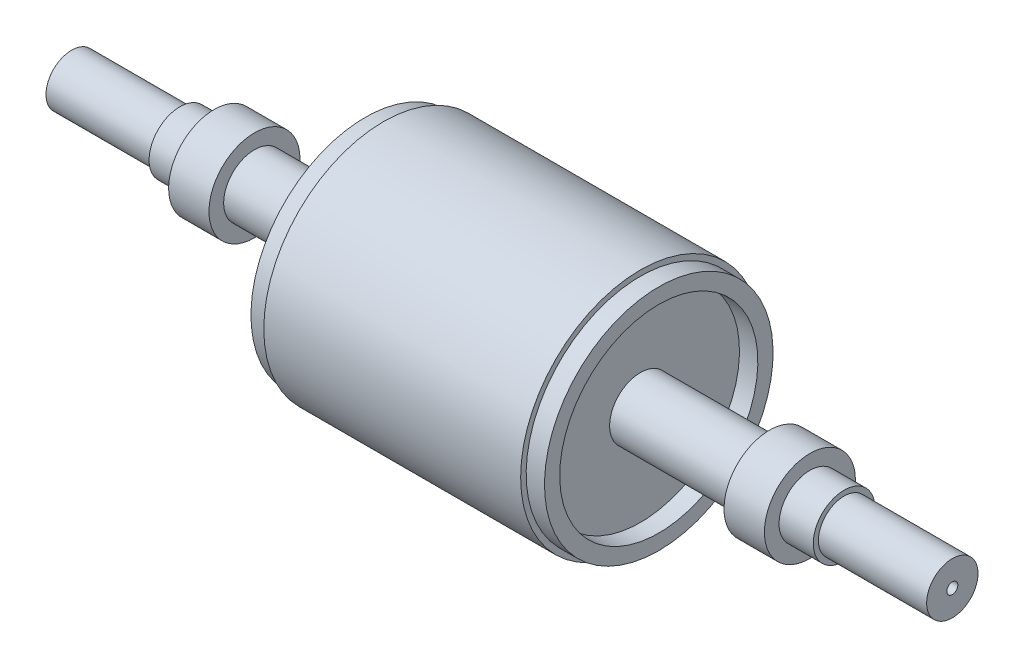
SolidWorks part; units mm, degrees
material "AISI 304"
ref_plane "Front Plane" through (0, 0, 0) normal (0, 0, 1) x (1, 0, 0)
ref_plane "Top Plane" through (0, 0, 0) normal (0, 1, 0) x (1, 0, 0)
ref_plane "Right Plane" through (0, 0, 0) normal (1, 0, 0) x (0, 0, -1)
sketch "Sketch1" plane through (0, 0, 0) normal (0, 0, 1) x (1, 0, 0)
  line L1 (20.4727, 9.9493) -> (90.4727, 9.9493)
  line L2 (15.4727, 8.4493) -> (15.4727, -14.2944)
  line L7 (15.4727, 8.4493) -> (20.4727, 8.4493)
  line L8 (20.4727, 9.9493) -> (20.4727, 8.4493)
  line L13 (15.4727, -14.2944) -> (-14.7073, -14.2944)
  line L16 (-64.5273, -15.6944) -> (-64.5273, -22.6944)
  line L17 (175.4752, -22.6944) -> (175.4752, -15.6944)
  line L20 (-64.5273, -15.6944) -> (-35.0273, -15.6944)
  line L21 (-35.0273, -14.2944) -> (-35.0273, -15.6944)
  line L25 (145.9752, -14.2944) -> (145.9752, -15.6944)
  line L26 (175.4752, -15.6944) -> (145.9752, -15.6944)
  line L27 (175.4752, -15.6944) -> (175.4752, -22.6944)
  line L28 (-64.5273, -22.6944) -> (175.4752, -22.6944)
  line L29 (95.4752, -14.2944) -> (125.6527, -14.2944)
  line L30 (90.4727, 9.9493) -> (90.4752, 8.4493)
  line L31 (95.4752, 8.4578) -> (90.4752, 8.4493)
  line L32 (95.4752, 8.4578) -> (95.4752, -14.2944)
  line L33 (-25.7073, -14.2944) -> (-35.0273, -14.2944)
  line L34 (-25.7073, -10.2944) -> (-14.7073, -10.2944)
  line L35 (-25.7073, -10.2944) -> (-25.7073, -14.2944)
  line L37 (-14.7073, -10.2944) -> (-14.7073, -14.2944)
  line L38 (136.6527, -14.2944) -> (145.9752, -14.2944)
  line L39 (125.6527, -10.2944) -> (136.6527, -10.2944)
  line L40 (125.6527, -10.2944) -> (125.6527, -14.2944)
  line L42 (136.6527, -10.2944) -> (136.6527, -14.2944)
  dimension "D2" = 11
  dimension "D3" = 1.5
  dimension "D4" = 5
  dimension "D5" = 7
  dimension "D6" = 9.3225
  dimension "D7" = 29.5
  dimension "D8" = 9.32
  dimension "D9" = 140.36
  dimension "D10" = 30.1775
  dimension "D11" = 80
  dimension "D12" = 29.5
  dimension "D13" = 11
  dimension "D14" = 1.5
  dimension "D15" = 5
  dimension "D16" = 4
  dimension "D17" = 70
  dimension "D18" = 90
  dimension "D19" = 7
  dimension "D20" = 1.4
  dimension "D21" = 30.18
  dimension "D22" = 1.4
  dimension "D23" = 4
revolve "Revolve1" add sketch "Sketch1" angle 360 about L28
sketch "Sketch2" plane through (15.4727, 0, 0) normal (-1, 0, 0) x (0, 0, 1)
  circle A0 centre (0, -22.6944) radius 8.4
  circle A1 centre (0, -22.6944) radius 27
extrude "Cut-Extrude1" cut sketch "Sketch2" against normal blind 5
sketch "Sketch3" plane through (95.4752, 0, 0) normal (1, 0, 0) x (0, 0, -1)
  circle A0 centre (0, -22.6944) radius 27
  circle A1 centre (0, -22.6944) radius 8.4
extrude "Cut-Extrude2" cut sketch "Sketch3" against normal blind 5
sketch "Sketch4" plane through (-64.5273, 0, 0) normal (-1, 0, 0) x (0, 0, 1)
  circle A0 centre (0, -22.6944) radius 1.5
extrude "Cut-Extrude3" cut sketch "Sketch4" against normal blind 5
sketch "Sketch6" plane through (175.4752, 0, 0) normal (1, 0, 0) x (0, 0, -1)
  circle A0 centre (0, -22.6944) radius 1.5
extrude "Cut-Extrude4" cut sketch "Sketch6" against normal blind 5
